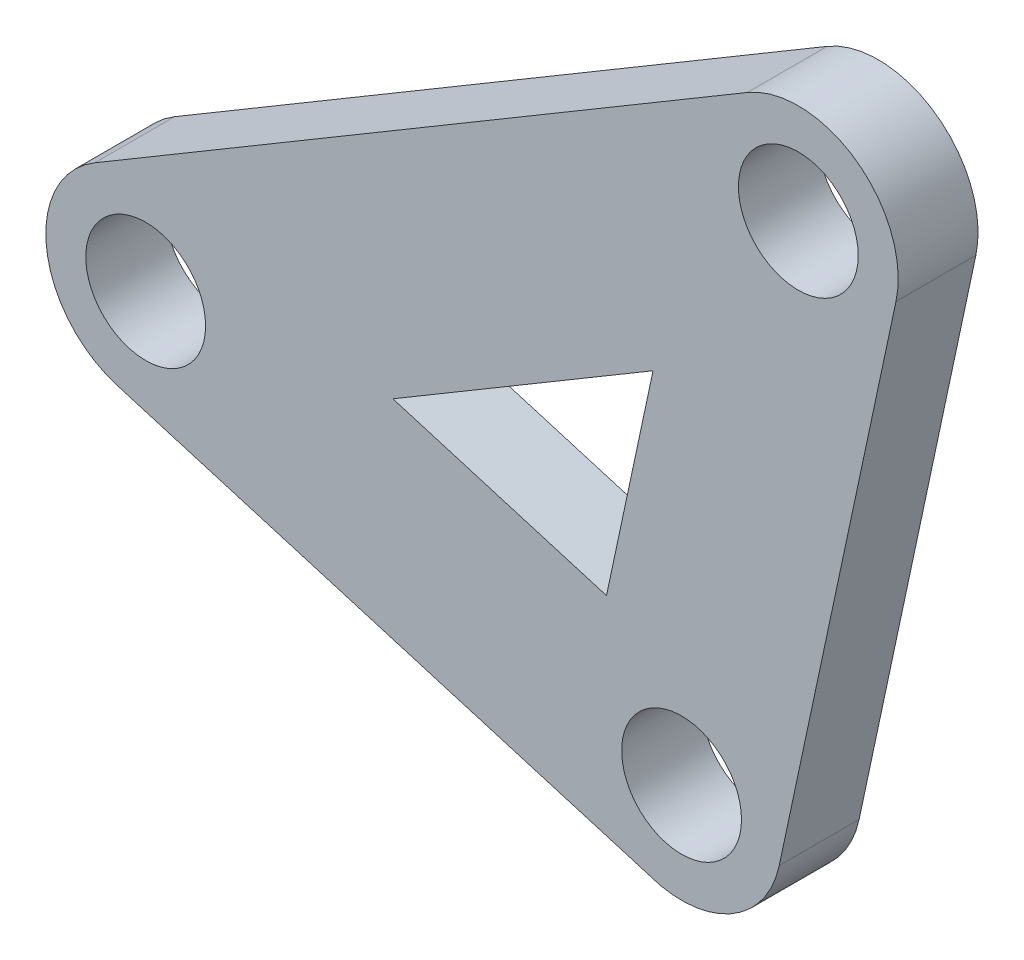
SolidWorks part; units mm, degrees
ref_plane "Plan de face" through (0, 0, 0) normal (0, 0, 1) x (1, 0, 0)
ref_plane "Plan de dessus" through (0, 0, 0) normal (0, 1, 0) x (1, 0, 0)
ref_plane "Plan de droite" through (0, 0, 0) normal (1, 0, 0) x (0, 0, -1)
sketch "Esquisse1" plane through (0, 0, 0) normal (0, 0, 1) x (1, 0, 0)
  line L0 (-29.4175, 2.9965) -> (-16, -1) construction
  line L1 (-28.7038, 5.3924) -> (-15.2863, 1.396)
  line L2 (-30.1311, 0.6005) -> (-16.7137, -3.396)
  line L3 (-16, -1) -> (-13.0771, 12.6915) construction
  line L4 (-18.4449, -0.4781) -> (-15.522, 13.2134)
  line L5 (-13.5551, -1.5219) -> (-10.6322, 12.1695)
  line L6 (-13.0771, 12.6915) -> (-29.4175, 2.9965) construction
  line L7 (-11.8015, 10.5414) -> (-28.1418, 0.8464)
  line L8 (-14.3528, 14.8415) -> (-30.6931, 5.1465)
  line L9 (-30.6931, 5.1465) -> (-14.3528, 14.8415)
  line L10 (-10.6322, 12.1695) -> (-13.5551, -1.5219)
  line L11 (-30.1311, 0.6005) -> (-16.5219, -3.4449)
  line L12 (-16.7148, 7.6263) -> (-23.2285, 3.7616)
  line L13 (-23.2285, 3.7616) -> (-17.8799, 2.1685)
  line L14 (-17.8799, 2.1685) -> (-16.7148, 7.6263)
  arc A0 (-28.7038, 5.3924) -> (-30.1311, 0.6005) centre (-29.4175, 2.9965) ccw
  arc A1 (-16.7137, -3.396) -> (-15.2863, 1.396) centre (-16, -1) ccw
  arc A2 (-18.4449, -0.4781) -> (-13.5551, -1.5219) centre (-16, -1) ccw
  arc A3 (-10.6322, 12.1695) -> (-15.522, 13.2134) centre (-13.0771, 12.6915) ccw
  arc A4 (-11.8015, 10.5414) -> (-14.3528, 14.8415) centre (-13.0771, 12.6915) ccw
  arc A5 (-30.6931, 5.1465) -> (-28.1418, 0.8464) centre (-29.4175, 2.9965) ccw
  point P4 (-22.7087, 0.9982)
  point P9 (-14.5386, 5.8457)
  point P18 (-21.2473, 7.844)
  point P25 (-16.7148, 7.6263)
  point P26 (-23.2285, 3.7616)
  point P27 (-17.8799, 2.1685)
  dimension "D1" = 5
  dimension "D2" = 5
  dimension "D3" = 5
extrude "Boss.-Extru.1" add sketch "Esquisse1" against normal blind 2 contours A3 L8 A0 L1 L7 L4 | A0 A5 L7 L1 | A5 L11 A2 L4 L1 L7 | L4 A2 L11 A1 L1 | A4 L7 L4 L1 A1 L5 | L7 A4 A3 L4
sketch "Esquisse2" plane through (0, 0, 0) normal (0, 0, 1) x (1, 0, 0)
  circle A0 centre (-29.4175, 2.9965) radius 1.5
  circle A1 centre (-16, -1) radius 1.5
  circle A2 centre (-13.0771, 12.6915) radius 1.5
  dimension "D1" = 3
  dimension "D2" = 3
  dimension "D3" = 3
extrude "Enlèv. mat.-Extru.1" cut sketch "Esquisse2" against normal blind 2
